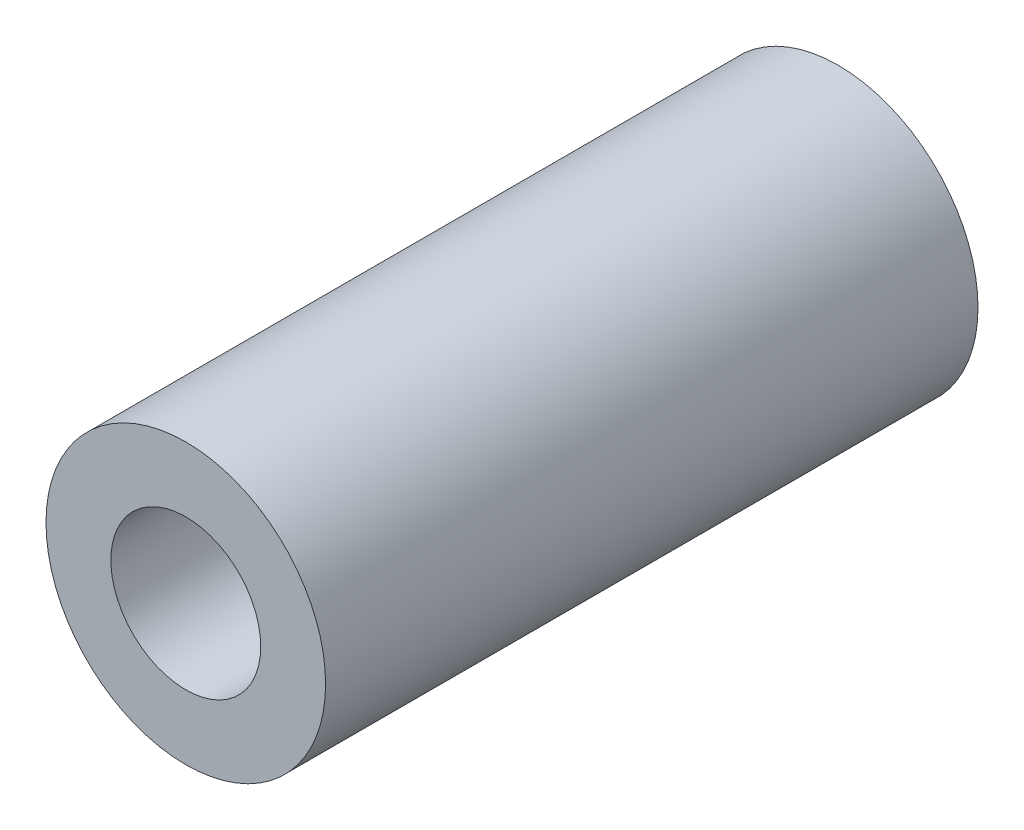
SolidWorks part; units mm, degrees
material "6061-T6 (SS)"
ref_plane "Front Plane" through (0, 0, 0) normal (0, 0, 1) x (1, 0, 0)
ref_plane "Top Plane" through (0, 0, 0) normal (0, 1, 0) x (1, 0, 0)
ref_plane "Right Plane" through (0, 0, 0) normal (1, 0, 0) x (0, 0, -1)
sketch "Sketch1" plane through (0, 0, 0) normal (0, 0, 1) x (1, 0, 0)
  circle A0 centre (0, 0) radius 4.7625
  dimension "D1" = 9.525
extrude "Boss-Extrude1" add sketch "Sketch1" along normal blind 22.225
hole_wizard "#10 Clearance Hole1" positions "Sketch2" profile "Sketch3" hole size "#10" standard "ANSI Inch" end condition through all
sketch "Sketch2" plane through (0, 0, 22.225) normal (0, 0, 1) x (1, 0, 0)
  point P0 (0, 0)
sketch "Sketch3" plane through (0, 0, 22.225) normal (1, 0, 0) x (0, -1, 0)
  line L0 (0, 0) -> (0, 22.225)
  line L1 (0, 22.225) -> (2.5527, 22.225)
  line L2 (2.5527, 22.225) -> (2.5527, 0)
  line L5 (2.5527, 0) -> (0, 0)
  line L11 (0, -6.35) -> (0, 107.95) construction
  dimension "Thru Hole Dia." = 5.1054
  dimension "Thru Hole Depth" = 22.225
